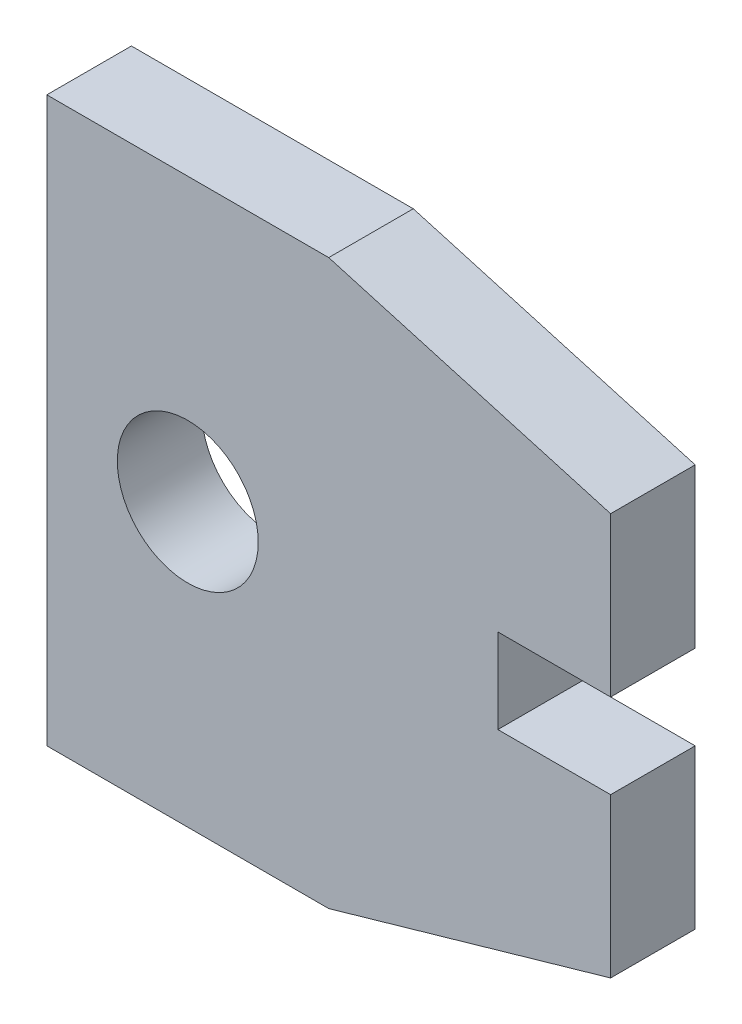
SolidWorks part; units mm, degrees
ref_plane "Front Plane" through (0, 0, 0) normal (0, 0, 1) x (1, 0, 0)
ref_plane "Top Plane" through (0, 0, 0) normal (0, 1, 0) x (1, 0, 0)
ref_plane "Right Plane" through (0, 0, 0) normal (1, 0, 0) x (0, 0, -1)
sketch "Sketch1" plane through (0, 0, 0) normal (0, 0, 1) x (1, 0, 0)
  line L0 (0, 10) -> (10, 7.1325)
  line L1 (-10, 10) -> (0, 10)
  line L2 (-10, 10) -> (-10, -10)
  line L3 (-10, -10) -> (0, -10)
  line L4 (10, 7.1325) -> (10, 2.5)
  line L5 (-10, 10) -> (10, -10) construction
  line L6 (-10, -10) -> (10, 10) construction
  line L7 (5, -2.5) -> (10, -2.5)
  line L8 (5, -2.5) -> (5, 2.5)
  line L9 (5, 2.5) -> (10, 2.5)
  line L10 (10, -2.5) -> (10, -7.1325)
  line L11 (5, -2.5) -> (15, 3.5) construction
  line L12 (5, 2.5) -> (14.9498, -1.4997) construction
  line L13 (0, -10) -> (10, -7.1325)
  line L14 (0, 0) -> (10, 0) construction
  circle A0 centre (-5, 0) radius 2.5
  point P0 (0, 0)
  point P8 (9.9901, 0.494)
  point P21 (5, 0)
  dimension "D3" = 5
  dimension "D1" = 20
  dimension "D2" = 20
  dimension "D4" = 5
  dimension "D5" = 5
  dimension "D6" = 10
  dimension "D7" = 16
  dimension "D8" = 5
extrude "Boss-Extrude1" add sketch "Sketch1" along normal blind 3
sketch "Sketch2" plane through (0, 0, 0) normal (0, 0, -1) x (-1, 0, 0)
  line L0 (-5, -2.5) -> (-5, 2.5) construction
  line L2 (-10, 2.5) -> (-5, 2.5)
  line L3 (-10, 2.5) -> (-10, 1.5)
  line L4 (-10, 1.5) -> (-5, 1.5)
  line L5 (-5, 2.5) -> (-5, 1.5)
  line L6 (-10, -2.5) -> (-5, -2.5)
  line L7 (-10, -2.5) -> (-10, -1.5)
  line L8 (-10, -1.5) -> (-5, -1.5)
  line L9 (-5, -2.5) -> (-5, -1.5)
  dimension "D1" = 1
  dimension "D2" = 1
extrude "Boss-Extrude2" add sketch "Sketch2" against normal blind 3
sketch "Sketch3" plane through (0, 0, 0) normal (0, 0, -1) x (-1, 0, 0)
  line L0 (-10, 1.5) -> (-5, 1.5) construction
  line L1 (-6, 1.5) -> (-5, 1.5)
  line L2 (-6, 1.5) -> (-6, -1.5)
  line L3 (-6, -1.5) -> (-5, -1.5)
  line L4 (-5, 1.5) -> (-5, -1.5)
  dimension "D1" = 1
extrude "Boss-Extrude3" add sketch "Sketch3" against normal blind 3
